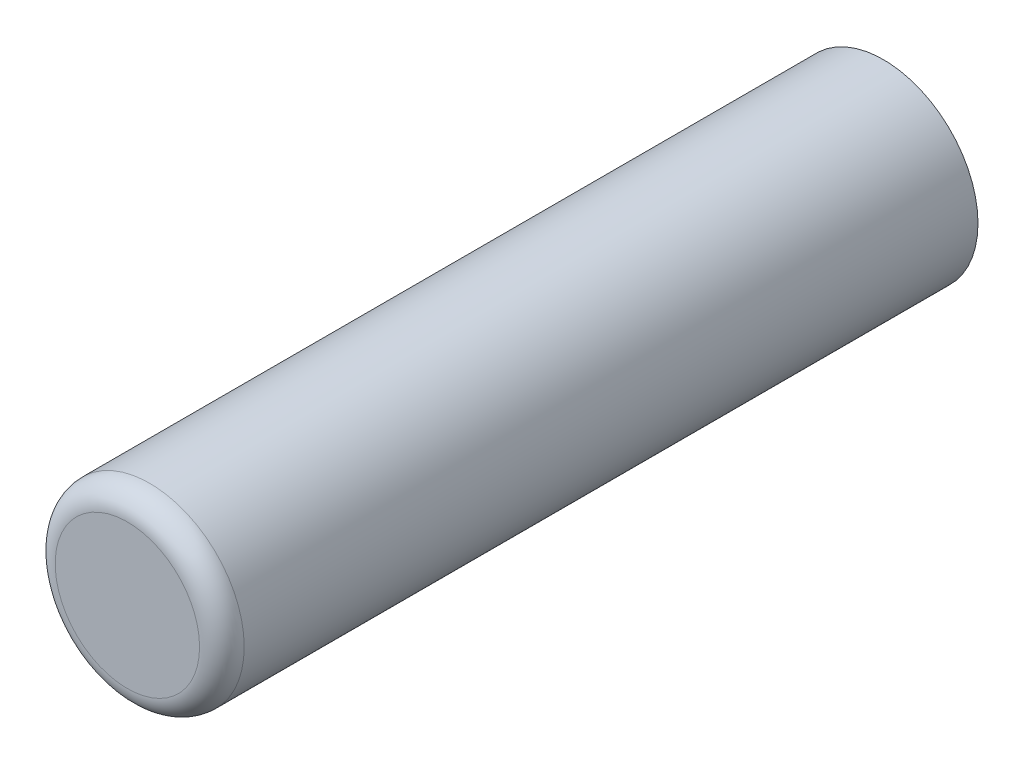
SolidWorks part; units mm, degrees
material "6061 Alloy"
ref_plane "Front Plane" through (0, 0, 0) normal (0, 0, 1) x (1, 0, 0)
ref_plane "Top Plane" through (0, 0, 0) normal (0, 1, 0) x (1, 0, 0)
ref_plane "Right Plane" through (0, 0, 0) normal (1, 0, 0) x (0, 0, -1)
sketch "Sketch1" plane through (0, 0, 0) normal (0, 0, 1) x (1, 0, 0)
  circle A0 centre (0, 0) radius 3.175
  dimension "D1" = 6.35
extrude "Boss-Extrude1" add sketch "Sketch1" along normal blind 25.4
sketch "Sketch2" plane through (0, 0, 0) normal (0, 0, -1) x (-1, 0, 0)
  line L1 (0, 0) -> (0, 3.818) construction
  line L2 (0, 3.4925) -> (0, -3.4925) construction
  circle A0 centre (-0.8, 0) radius 0.6
  circle A1 centre (0.8, 0) radius 0.6
  dimension "D2" = 1.2
  dimension "D1" = 1.6
  dimension "D3" = 0
extrude "Boss-Extrude2" [suppressed] add sketch "Sketch2" along normal blind 125
fillet "Fillet1" radius 0.75 1 edges at (3.175, 0, 25.4)
